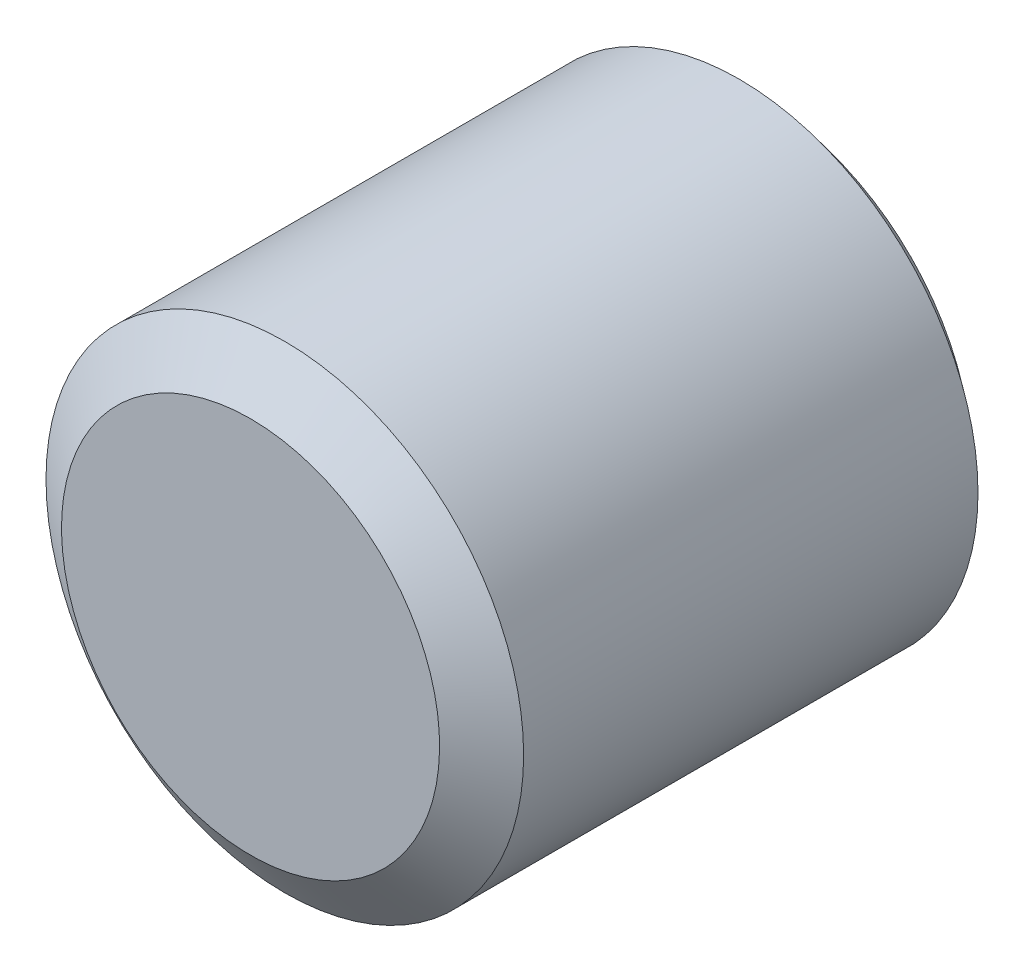
SolidWorks part; units mm, degrees
ref_plane "Front Plane" through (0, 0, 0) normal (0, 0, 1) x (1, 0, 0)
ref_plane "Top Plane" through (0, 0, 0) normal (0, 1, 0) x (1, 0, 0)
ref_plane "Right Plane" through (0, 0, 0) normal (1, 0, 0) x (0, 0, -1)
sketch "Sketch1" plane through (0, 0, 0) normal (1, 0, 0) x (0, 0, -1)
  line L0 (0, 0) -> (0, 11.0816)
  line L1 (0, 11.0816) -> (2.0098, 14)
  line L2 (2.0098, 14) -> (28.6451, 14)
  line L3 (28.6451, 14) -> (30, 12.2761)
  line L4 (30, 12.2761) -> (30, 0)
  line L5 (30, 0) -> (0, 0)
  point P3 (28.6451, 14)
  dimension "D1" = 14
  dimension "D2" = 30
revolve "Revolve1" add sketch "Sketch1" angle 360 about L5
